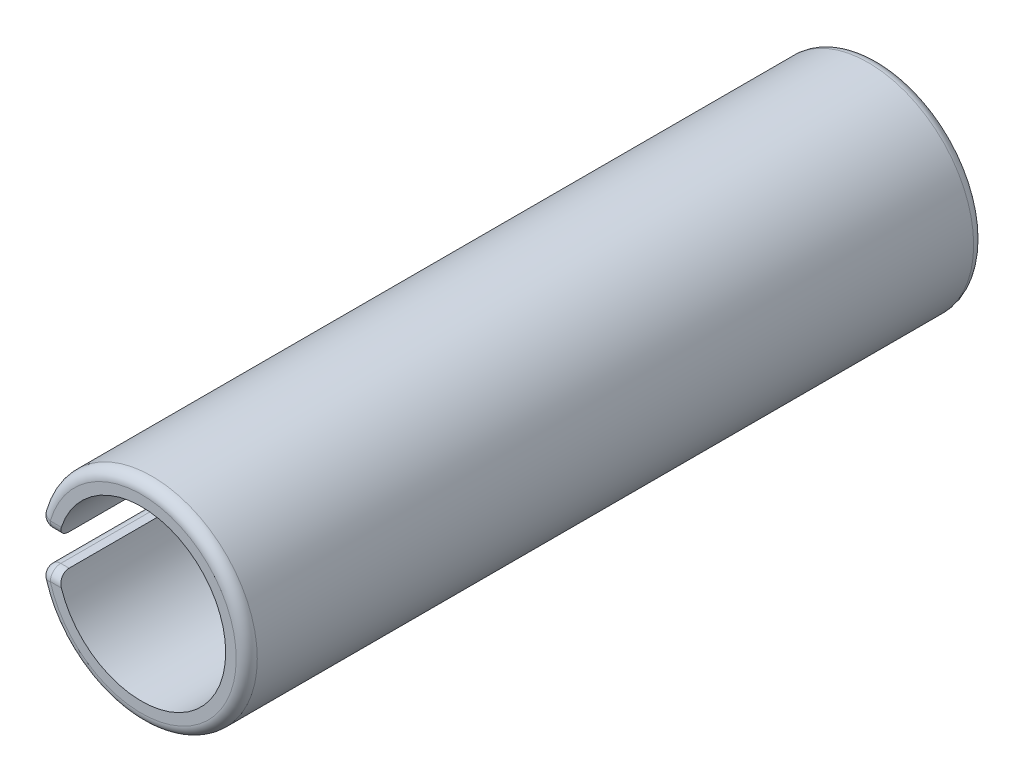
SolidWorks part; units mm, degrees
ref_plane "Plano frontal" through (0, 0, 0) normal (0, 0, 1) x (1, 0, 0)
ref_plane "Plano superior" through (0, 0, 0) normal (0, 1, 0) x (1, 0, 0)
ref_plane "Plano direito" through (0, 0, 0) normal (1, 0, 0) x (0, 0, -1)
sketch "Esboço1" plane through (0, 0, 0) normal (0, 0, 1) x (1, 0, 0)
  line L0 (-0.865, 0.1496) -> (-0.7859, 0.1493)
  line L1 (-0.865, -0.1496) -> (-0.7859, -0.1493)
  arc A0 (-0.9608, -0.2773) -> (-0.9608, 0.2773) centre (0, 0) ccw
  arc A1 (-0.7859, -0.1493) -> (-0.7859, 0.1493) centre (0, 0) ccw
  arc A2 (-0.9608, -0.2773) -> (-0.865, -0.1496) centre (-0.8647, -0.2496) cw
  arc A3 (-0.9608, 0.2773) -> (-0.865, 0.1496) centre (-0.8647, 0.2496) ccw
  dimension "D1" = 1.6
  dimension "D2" = 2
  dimension "D3" = 0.1
extrude "Ressalto-extrusão1" add sketch "Esboço1" along normal blind 7
fillet "Filete1" radius 0.1 10 edges at (-0.8255, -0.1495, 0) (-0.9447, -0.1896, 0) (-0.8255, 0.1495, 0) (-0.9447, 0.1896, 0) (-0.8255, -0.1495, 7) (-0.9447, -0.1896, 7) (-0.8255, 0.1495, 7) (-0.9447, 0.1896, 7) (1, 0, 0) (1, 0, 7)
